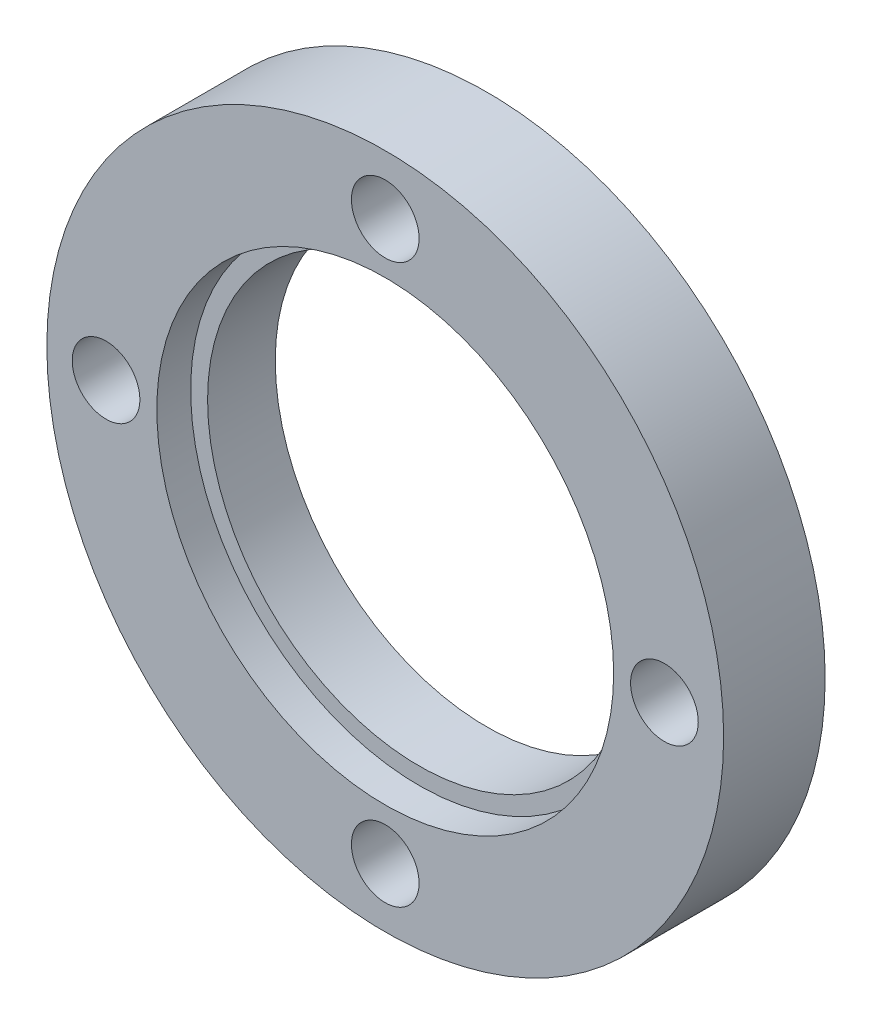
SolidWorks part; units mm, degrees
ref_plane "Front Plane" through (0, 0, 0) normal (0, 0, 1) x (1, 0, 0)
ref_plane "Top Plane" through (0, 0, 0) normal (0, 1, 0) x (1, 0, 0)
ref_plane "Right Plane" through (0, 0, 0) normal (1, 0, 0) x (0, 0, -1)
sketch "Sketch1" plane through (0, 0, 0) normal (0, 0, 1) x (1, 0, 0)
  circle A0 centre (0, 0) radius 40
  dimension "D1" = 80
extrude "Boss-Extrude1" add sketch "Sketch1" along normal blind 12
sketch "Sketch2" plane through (0, 0, 0) normal (0, 0, -1) x (-1, 0, 0)
  circle A0 centre (0, 0) radius 25
  dimension "D1" = 50
extrude "Cut-Extrude1" cut sketch "Sketch2" against normal through all contours A0
sketch "Sketch3" plane through (0, 0, 12) normal (0, 0, 1) x (1, 0, 0)
  circle A0 centre (0, 0) radius 33 construction
  circle A1 centre (-33, 0) radius 4
  circle A2 centre (0, 33) radius 4
  circle A3 centre (33, 0) radius 4
  circle A4 centre (0, -33) radius 4
  point P14 (0, 0)
  dimension "D1" = 8
  dimension "D3" = 33
  dimension "D2" = 4
extrude "Cut-Extrude2" cut sketch "Sketch3" against normal through all
sketch "Sketch4" plane through (0, 0, 12) normal (0, 0, 1) x (1, 0, 0)
  circle A0 centre (0, 0) radius 25
  circle A1 centre (0, 0) radius 27
  dimension "D1" = 2
extrude "Cut-Extrude3" cut sketch "Sketch4" against normal blind 4
